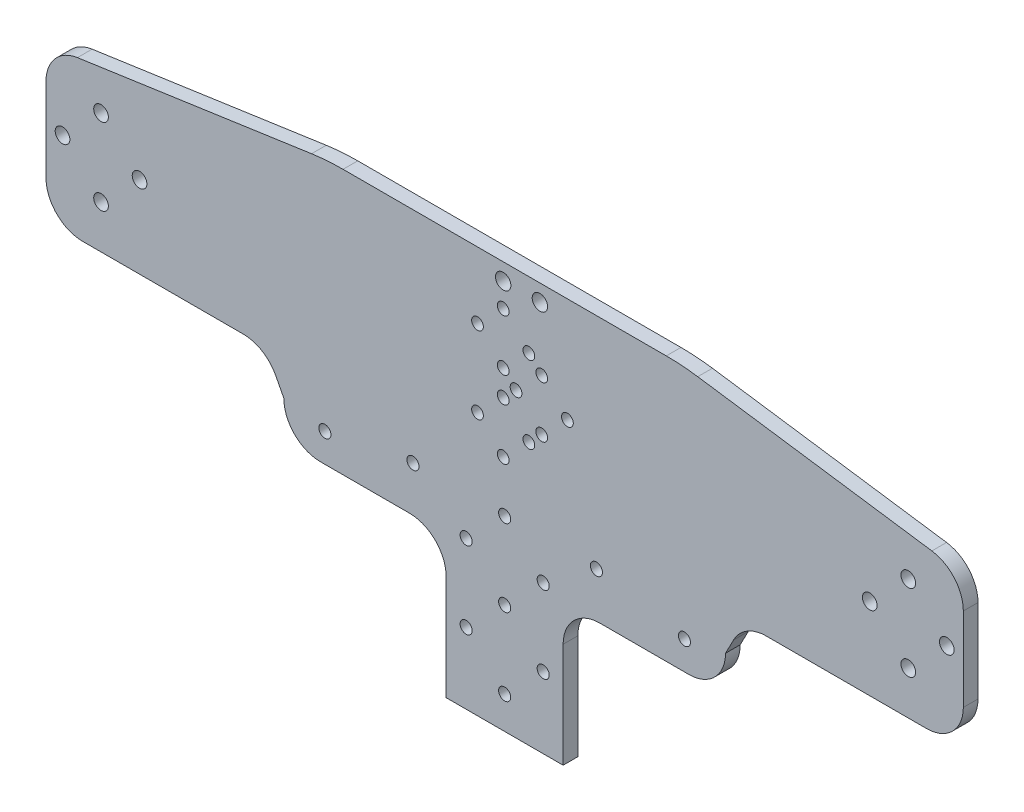
SolidWorks part; units mm, degrees
ref_plane "前视基准面" through (0, 0, 0) normal (0, 0, 1) x (1, 0, 0)
ref_plane "上视基准面" through (0, 0, 0) normal (0, 1, 0) x (1, 0, 0)
ref_plane "右视基准面" through (0, 0, 0) normal (1, 0, 0) x (0, 0, -1)
other "Configuration Table"
sketch "草图1" plane through (0, 0, 0) normal (0, 0, 1) x (1, 0, 0)
  line L16 (-71.2575, -5.3843) -> (-115, -5.3843)
  line L19 (-125, 4.6157) -> (-125, 27.3731)
  line L25 (15.9335, -35.0094) -> (15.9335, -63.561)
  line L26 (50.1835, -25.0094) -> (25.9335, -25.0094)
  line L29 (125, 4.6157) -> (125, 27.3731)
  line L35 (71.2575, -5.3843) -> (115, -5.3843)
  line L38 (-62.3834, -10.7745) -> (-60.1835, -15.0094)
  line L41 (60.1835, -15.0094) -> (62.3834, -10.7745)
  line L44 (0.1599, 47.1052) -> (-44.0428, 47.1052)
  line L45 (-52.6219, 46.4887) -> (-116.4299, 37.2704)
  line L46 (-111.6556, 16.9345) -> (148.2953, 11.8822) construction
  line L47 (125, 4.6157) -> (125, 36.0322)
  line L48 (52.6219, 46.4887) -> (116.4299, 37.2704)
  line L49 (-0.1599, 47.1052) -> (44.0428, 47.1052)
  line L84 (-50.1835, -25.0094) -> (-25.9335, -25.0094)
  line L85 (-15.9335, -35.0094) -> (-15.9335, -63.561)
  line L86 (-15.9335, -63.561) -> (15.9335, -63.561)
  line L87 (0, -63.561) -> (0, 95.9708) construction
  circle A114 centre (-110, 16.9024) radius 10.5 construction
  circle A115 centre (-110, 27.4024) radius 2
  circle A116 centre (-99.5, 16.9024) radius 2
  circle A117 centre (-110, 6.4024) radius 2
  circle A118 centre (-120.5, 16.9024) radius 2
  arc A133 (-25.9335, -25.0094) -> (-15.9335, -35.0094) centre (-25.9335, -35.0094) cw
  arc A136 (-50.1835, -25.0094) -> (-60.1835, -15.0094) centre (-50.1835, -15.0094) cw
  circle A141 centre (110, 16.9024) radius 10.5 construction
  arc A143 (50.1835, -25.0094) -> (60.1835, -15.0094) centre (50.1835, -15.0094) ccw
  arc A144 (25.9335, -25.0094) -> (15.9335, -35.0094) centre (25.9335, -35.0094) ccw
  circle A145 centre (120.5, 16.9024) radius 2
  circle A146 centre (110, 6.4024) radius 2
  circle A147 centre (99.5, 16.9024) radius 2
  circle A148 centre (110, 27.4024) radius 2
  circle A150 centre (0, -54.7094) radius 1.65
  circle A151 centre (-10.5, -44.2094) radius 1.65
  circle A152 centre (10.5, -44.2094) radius 1.65
  circle A153 centre (0, -33.7094) radius 1.65
  circle A154 centre (0, -12.7094) radius 1.65
  circle A155 centre (-10.5, -23.2094) radius 1.65
  circle A158 centre (-25, -12.7094) radius 1.65
  circle A159 centre (-49, -17.2094) radius 1.65
  circle A160 centre (10.5, -23.2094) radius 1.65
  circle A162 centre (25, -12.7094) radius 1.65
  circle A163 centre (49, -17.2094) radius 1.65
  arc A168 (125, 4.6157) -> (115, -5.3843) centre (115, 4.6157) cw
  arc A169 (-115, -5.3843) -> (-125, 4.6157) centre (-115, 4.6157) cw
  circle A170 centre (9.6, 42.5322) radius 2.1
  circle A171 centre (-0.4, 42.5322) radius 2.1
  circle A172 centre (-0.4, 1.0322) radius 1.6
  circle A173 centre (-7.4, 8.0322) radius 1.6
  circle A174 centre (6.6, 8.0322) radius 1.6
  circle A175 centre (10.1, 11.5322) radius 1.6
  circle A176 centre (-0.4, 15.0322) radius 1.6
  circle A177 centre (6.6, 29.0322) radius 1.6
  circle A178 centre (17.1, 18.5322) radius 1.6
  circle A179 centre (10.1, 25.5322) radius 1.6
  circle A180 centre (3.1, 18.5322) radius 1.6
  circle A181 centre (-0.4, 22.0322) radius 1.6
  circle A182 centre (-7.4, 29.0322) radius 1.6
  circle A183 centre (-0.4, 36.0322) radius 1.6
  arc A184 (62.3834, -10.7745) -> (71.2575, -5.3843) centre (71.2575, -15.3843) cw
  arc A185 (-71.2575, -5.3843) -> (-62.3834, -10.7745) centre (-71.2575, -15.3843) cw
  arc A186 (115, -5.3843) -> (125, 4.6157) centre (115, 4.6157) ccw
  arc A187 (125, 27.3731) -> (116.4299, 37.2704) centre (115, 27.3731) ccw
  arc A188 (-116.4299, 37.2704) -> (-125, 27.3731) centre (-115, 27.3731) ccw
  arc A189 (52.6219, 46.4887) -> (44.0428, 47.1052) centre (44.0428, -12.8948) ccw
  arc A190 (-44.0428, 47.1052) -> (-52.6219, 46.4887) centre (-44.0428, -12.8948) ccw
  point P11 (0, 0)
  point P13 (65.1835, -5.3843)
  point P43 (60.1835, -10.3086)
  point P44 (60.1835, -5.3843)
  point P45 (101.0375, 25.299)
  point P48 (-15.9335, -25.0094)
  point P50 (101.0375, -5.3843)
  point P51 (60.1835, -25.0094)
  point P52 (15.9335, -25.0094)
  point P60 (-60.1835, -25.0094)
  point P64 (-101.0375, -5.3843)
  point P67 (-101.0375, 25.299)
  point P73 (-60.1835, -5.3843)
  point P94 (125, -5.3843)
  point P97 (-125, -5.3843)
  point P126 (-65.1835, -5.3843)
  point P133 (48.3545, 47.1052)
  point P136 (-48.3545, 47.1052)
  point P284 (-60.1835, -10.3086)
  point P285 (0, -0.3086)
  point P324 (0, 43.7163)
  dimension "D3" = 4
  dimension "D7" = 3.3
  dimension "D11" = 3.2
  dimension "D1" = 220
  dimension "D2" = 21
  dimension "D4" = 31.867
  dimension "D5" = 10
  dimension "D6" = 250
  dimension "D8" = 10
  dimension "D9" = 4.2
  dimension "D10" = 4.2
extrude "凸台-拉伸1" add sketch "草图1" along normal blind 4 contours L44 A190 L45 A188 L19 A169 L16 A185 L38 A136 L84 A133 L85 L86 L25 A144 L26 A143 L41 A184 L35 A168 L29 A187 L48 A189 L49 A148 A146 A115 A116 A117 A118 A145 A147 A150 A151 A152
